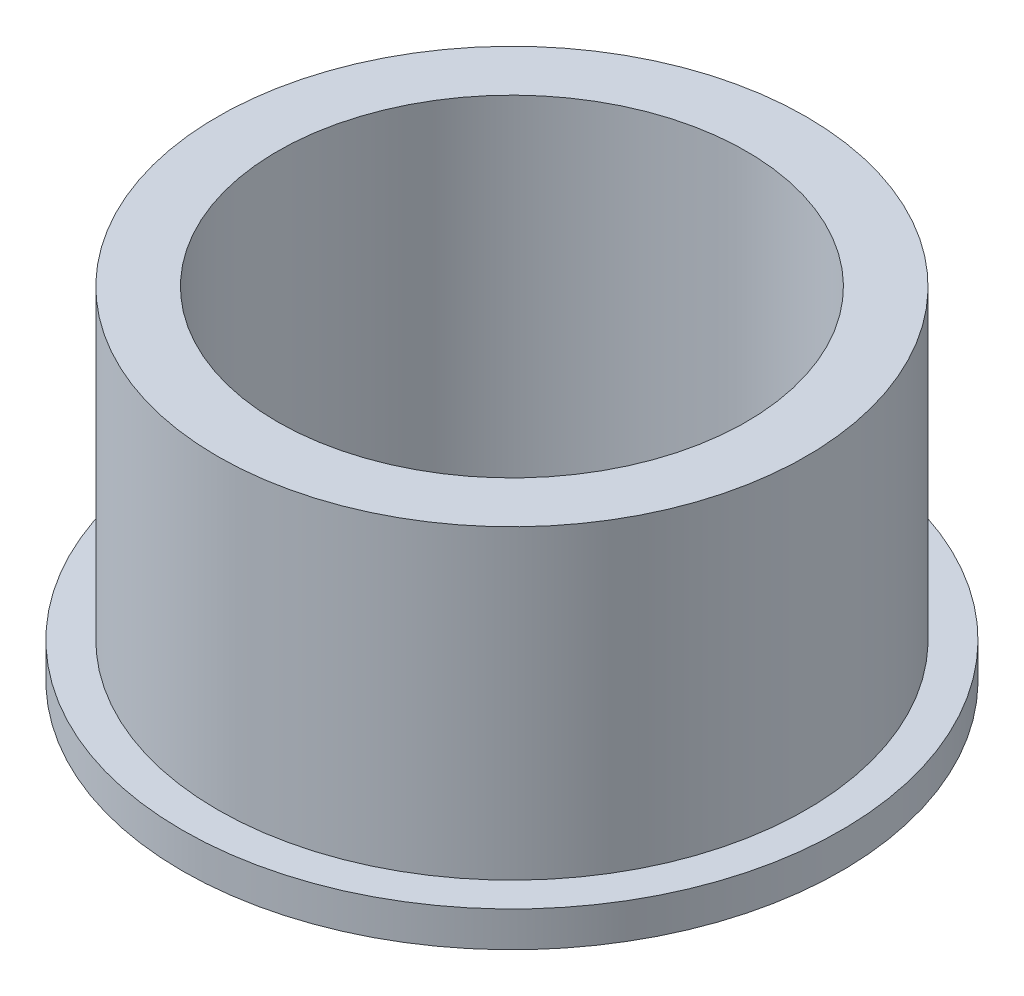
SolidWorks part; units mm, degrees
ref_plane "Front Plane" through (0, 0, 0) normal (0, 0, 1) x (1, 0, 0)
ref_plane "Top Plane" through (0, 0, 0) normal (0, 1, 0) x (1, 0, 0)
ref_plane "Right Plane" through (0, 0, 0) normal (1, 0, 0) x (0, 0, -1)
sketch "Sketch1" plane through (0, 0, 0) normal (1, 0, 0) x (0, 0, -1)
  line L0 (0, 7.4129) -> (0, -7.4237) construction
  line L1 (3.0353, 0) -> (4.2672, 0)
  line L2 (4.2672, 0) -> (4.2672, 0.4572)
  line L3 (4.2672, 0.4572) -> (3.81, 0.4572)
  line L4 (3.81, 0.4572) -> (3.81, 4.4196)
  line L5 (3.81, 4.4196) -> (3.0353, 4.4196)
  line L6 (3.0353, 4.4196) -> (3.0353, 0)
  dimension "D1" = 4.2672
  dimension "D2" = 3.81
  dimension "D3" = 3.0353
  dimension "D4" = 0.4572
  dimension "D5" = 4.4196
revolve "Revolve1" add sketch "Sketch1" angle 360 about L0
